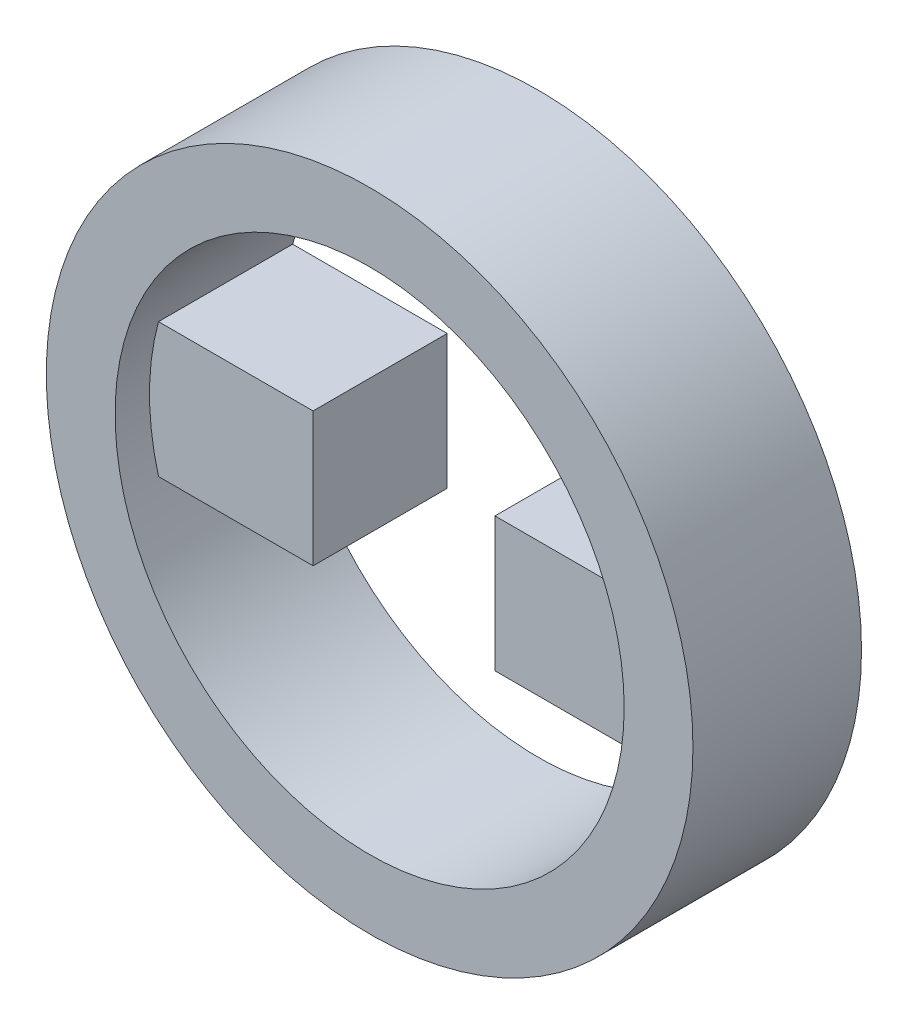
SolidWorks part; units mm, degrees
ref_plane "前视基准面" through (0, 0, 0) normal (0, 0, 1) x (1, 0, 0)
ref_plane "上视基准面" through (0, 0, 0) normal (0, 1, 0) x (1, 0, 0)
ref_plane "右视基准面" through (0, 0, 0) normal (1, 0, 0) x (0, 0, -1)
other "Configuration Table"
sketch "草图1" plane through (0, 0, 0) normal (0, 0, 1) x (1, 0, 0)
  circle A0 centre (0, 0) radius 7.4
  dimension "D1" = 14.8
extrude "拉伸-薄壁1" add sketch "草图1" along normal blind 4.9 thin contours A0
sketch "草图2" plane through (0, 0, 0) normal (0, 0, 1) x (1, 0, 0)
  line L0 (0, 0) -> (-4.1337, 0) construction
  line L1 (0, 0) -> (0, 4.8283) construction
  line L2 (8.1422, -1.95) -> (2.6437, -1.95)
  line L3 (-8.1422, 1.95) -> (-2.6437, 1.95)
  line L4 (-8.1422, 1.95) -> (-8.1422, -1.95)
  line L5 (-8.1422, -1.95) -> (-2.6437, -1.95)
  line L6 (-2.6437, 1.95) -> (-2.6437, -1.95)
  line L7 (-8.1422, 1.95) -> (-2.6437, -1.95) construction
  line L8 (-8.1422, -1.95) -> (-2.6437, 1.95) construction
  line L9 (2.6437, 1.95) -> (2.6437, -1.95)
  line L10 (8.1422, 1.95) -> (2.6437, 1.95)
  line L11 (8.1422, 1.95) -> (8.1422, -1.95)
  point P3 (-5.3929, 0)
  point P9 (-5.4961, 0)
  point P10 (0, 0)
  point P11 (-2.6437, 1.95)
  dimension "D1" = 3.9
extrude "凸台-拉伸1" add sketch "草图2" along normal blind 3.9
